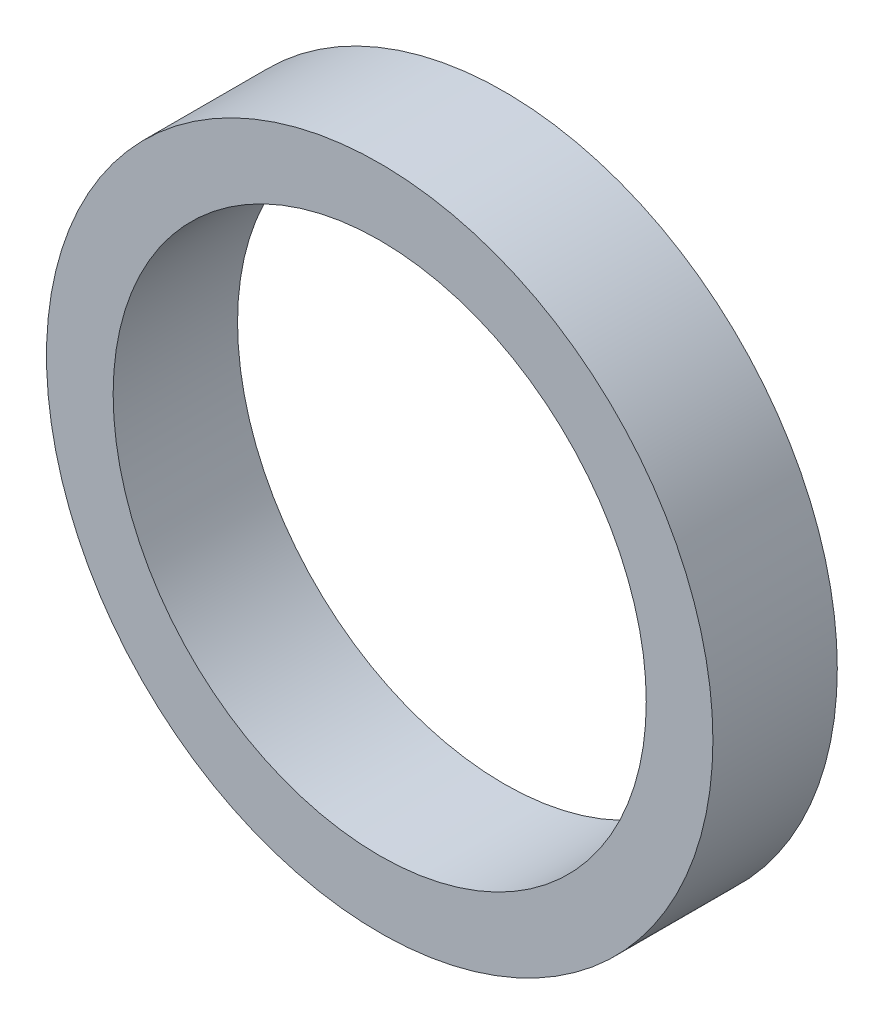
SolidWorks part; units mm, degrees
material "Acier non allié"
ref_plane "Plan de face" through (0, 0, 0) normal (0, 0, 1) x (1, 0, 0)
ref_plane "Plan de dessus" through (0, 0, 0) normal (0, 1, 0) x (1, 0, 0)
ref_plane "Plan de droite" through (0, 0, 0) normal (1, 0, 0) x (0, 0, -1)
sketch "Esquisse1" plane through (0, 0, 0) normal (0, 0, 1) x (1, 0, 0)
  circle A0 centre (0, 0) radius 6
  circle A1 centre (0, 0) radius 7.5
  dimension "D1" = 12
  dimension "D2" = 15
extrude "Extrusion1" add sketch "Esquisse1" along normal mid plane 2.8
